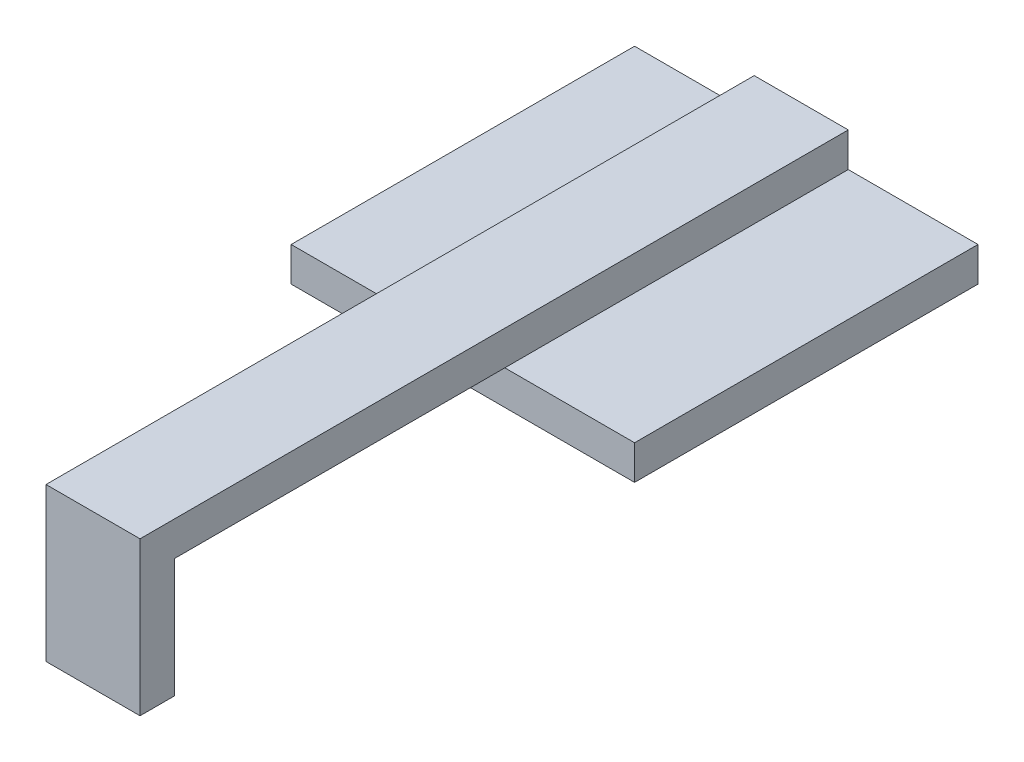
SolidWorks part; units mm, degrees
ref_plane "Alzado" through (0, 0, 0) normal (0, 0, 1) x (1, 0, 0)
ref_plane "Planta" through (0, 0, 0) normal (0, 1, 0) x (1, 0, 0)
ref_plane "Vista lateral" through (0, 0, 0) normal (1, 0, 0) x (0, 0, -1)
sketch "Croquis1" plane through (0, 0, 0) normal (0, 1, 0) x (1, 0, 0)
  line L1 (-15, 15) -> (15, 15)
  line L2 (-15, 15) -> (-15, -15)
  line L3 (-15, -15) -> (15, -15)
  line L4 (15, 15) -> (15, -15)
  line L5 (-15, 15) -> (15, -15) construction
  line L6 (-15, -15) -> (15, 15) construction
  point P0 (0, 0)
  dimension "D1" = 30
  dimension "D2" = 30
extrude "Saliente-Extruir1" add sketch "Croquis1" along normal blind 3
sketch "Croquis2" plane through (0, 3, 0) normal (0, 1, 0) x (1, 0, 0)
  line L0 (15, 15) -> (-15, 15) construction
  line L1 (-4.5492, 15) -> (3.6653, 15)
  line L2 (-4.5492, 15) -> (-4.5492, -43.8667)
  line L3 (-4.5492, -43.8667) -> (3.6653, -43.8667)
  line L4 (3.6653, 15) -> (3.6653, -43.8667)
extrude "Saliente-Extruir2" add sketch "Croquis2" along normal blind 3
sketch "Croquis3" plane through (0, 0, 43.8667) normal (0, 0, 1) x (1, 0, 0)
  line L0 (3.6653, 6) -> (3.6653, 3) construction
  line L1 (-4.5492, 6) -> (3.6653, 6)
  line L2 (-4.5492, 6) -> (-4.5492, -7.3918)
  line L3 (-4.5492, -7.3918) -> (3.6653, -7.3918)
  line L4 (3.6653, 6) -> (3.6653, -7.3918)
extrude "Saliente-Extruir3" add sketch "Croquis3" along normal blind 3
